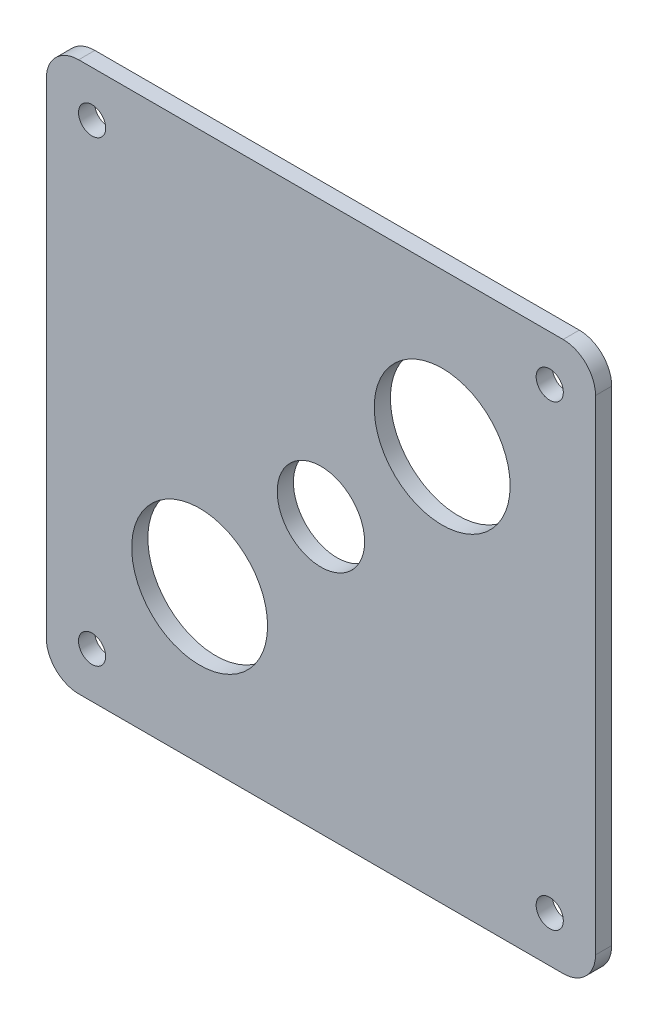
SolidWorks part; units mm, degrees
ref_plane "Front" through (0, 0, 0) normal (0, 0, 1) x (1, 0, 0)
ref_plane "Top" through (0, 0, 0) normal (0, 1, 0) x (1, 0, 0)
ref_plane "Right" through (0, 0, 0) normal (1, 0, 0) x (0, 0, -1)
sketch "Sketch1" plane through (0, 0, 0) normal (0, 0, 1) x (1, 0, 0)
  line L1 (-53.8815, -53.8815) -> (53.8815, -53.8815)
  line L2 (-53.8815, -53.8815) -> (-53.8815, 53.8815)
  line L3 (-53.8815, 53.8815) -> (53.8815, 53.8815)
  line L4 (53.8815, -53.8815) -> (53.8815, 53.8815)
  line L5 (-53.8815, -53.8815) -> (53.8815, 53.8815) construction
  line L6 (-53.8815, 53.8815) -> (53.8815, -53.8815) construction
  point P0 (0, 0)
  dimension "D1" = 152.4
extrude "Boss-Extrude1" add sketch "Sketch1" along normal blind 3.175 contours L2 L3 L4 L1
sketch "Sketch4" plane through (0, 0, 3.175) normal (0, 0, 1) x (1, 0, 0)
  line L0 (-53.8815, 0) -> (53.8815, 0) construction
  line L1 (-53.8815, -53.8815) -> (-53.8815, 53.8815) construction
  line L2 (53.8815, -53.8815) -> (53.8815, 53.8815) construction
  circle A0 centre (0, 0) radius 8.5725
  dimension "D1" = 17.145
extrude "Cut-Extrude2" cut sketch "Sketch4" against normal up to next
fillet "Fillet2" radius 6.35 4 edges at (53.8815, 53.8815, 1.5875) (-53.8815, 53.8815, 1.5875) (53.8815, -53.8815, 1.5875) (-53.8815, -53.8815, 1.5875)
sketch "Sketch5" plane through (0, 0, 0) normal (0, 0, -1) x (-1, 0, 0)
  circle A4 centre (44.9013, 44.9013) radius 2.665
  circle A5 centre (44.9013, -44.9013) radius 2.665
  circle A6 centre (-44.9013, -44.9013) radius 2.665
  circle A7 centre (-44.9013, 44.9013) radius 2.665
extrude "Cut-Extrude3" cut sketch "Sketch5" against normal up to next
sketch "Sketch6" plane through (0, 0, 3.175) normal (0, 0, 1) x (1, 0, 0)
  line L0 (33.676, 33.676) -> (23.7977, 23.7977) construction
  line L1 (23.7977, 23.7977) -> (-23.7977, -23.7977) construction
  line L2 (-23.7977, -23.7977) -> (-33.676, -33.676) construction
  line L3 (0, 0) -> (-44.9013, -44.9013) construction
  circle A0 centre (0, 0) radius 47.625 construction
  circle A1 centre (23.7977, 23.7977) radius 13.335
  circle A2 centre (-23.7977, -23.7977) radius 13.335
  dimension "D1" = 95.25
  dimension "D3" = 26.67
  dimension "D2" = 13.97
extrude "Cut-Extrude4" cut sketch "Sketch6" against normal up to next
